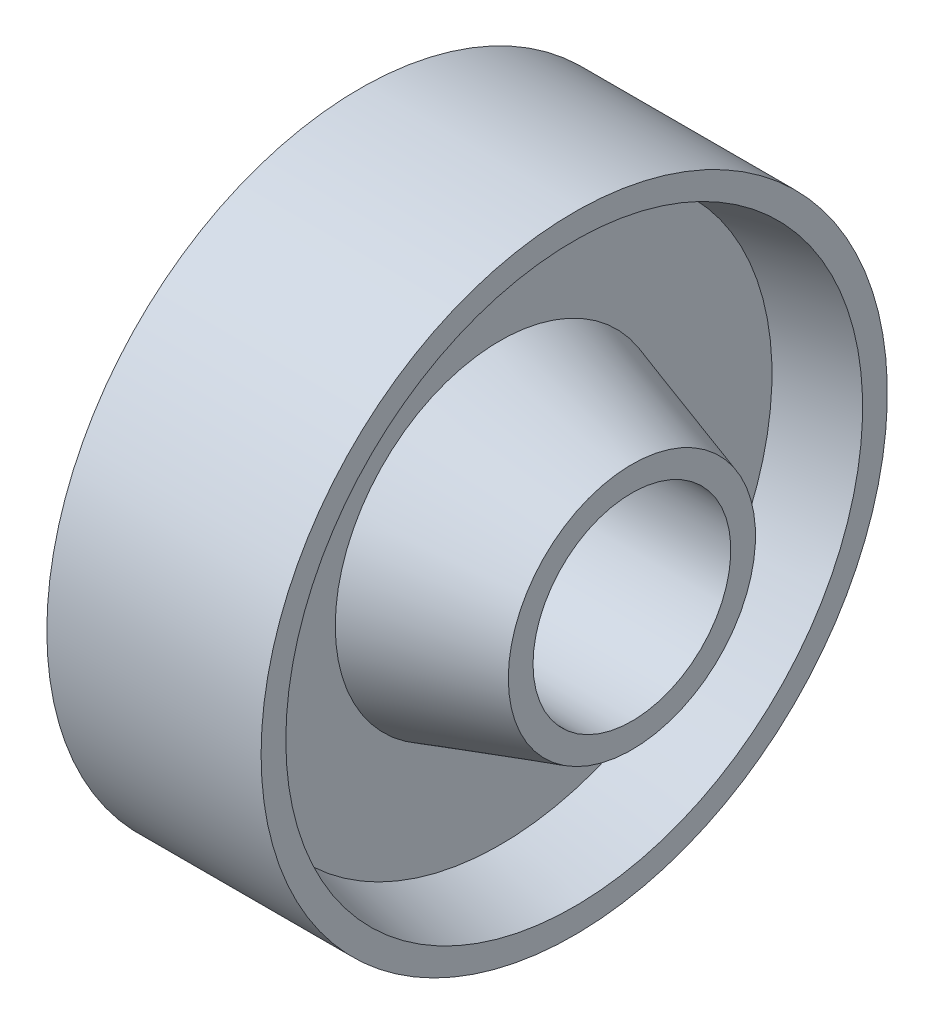
SolidWorks part; units mm, degrees
ref_plane "Front Plane" through (0, 0, 0) normal (0, 0, 1) x (1, 0, 0)
ref_plane "Top Plane" through (0, 0, 0) normal (0, 1, 0) x (1, 0, 0)
ref_plane "Right Plane" through (0, 0, 0) normal (1, 0, 0) x (0, 0, -1)
sketch "Sketch1" plane through (0, 0, 0) normal (0, 0, 1) x (1, 0, 0)
  line L1 (4, 20) -> (4, 33)
  line L2 (-4, 20) -> (-4, 33)
  line L3 (13, 35) -> (13, 38)
  line L4 (-13, 35) -> (-13, 38)
  line L5 (-13, 38) -> (13, 38)
  line L6 (-25.4316, 0) -> (26.664, 0) construction
  line L8 (13, 35) -> (4, 33)
  line L9 (-13, 35) -> (-4, 33)
  line L14 (-20, 12) -> (20, 12)
  line L15 (20, 15) -> (4, 20)
  line L18 (-20, 12) -> (-20, 15)
  line L20 (-20, 15) -> (-4, 20)
  line L23 (20, 12) -> (20, 15)
  point P3 (4, -46.7292)
  point P4 (4, 38)
  point P5 (-4, -46.7292)
  point P6 (-4, 38)
  point P7 (13, -46.7292)
  point P9 (-13, -46.7292)
  point P13 (-13, 45.1562)
  point P14 (13, 45.1562)
  point P21 (-31.1267, 12)
  point P22 (34.5245, 12)
  point P25 (20, -46.7292)
  point P26 (20, 38)
  point P27 (-20, -46.7292)
  point P28 (-20, 38)
  dimension "D5" = 13
  dimension "D6" = 35
  dimension "D7" = 33
  dimension "D8" = 33
  dimension "D9" = 35
  dimension "D14" = 38
  dimension "D1" = 4
  dimension "D2" = 13
  dimension "D3" = 20
  dimension "D4" = 4
  dimension "D10" = 20
  dimension "D11" = 12
  dimension "D12" = 15
  dimension "D13" = 20
revolve "Revolve1" add sketch "Sketch1" angle 360 about L6
